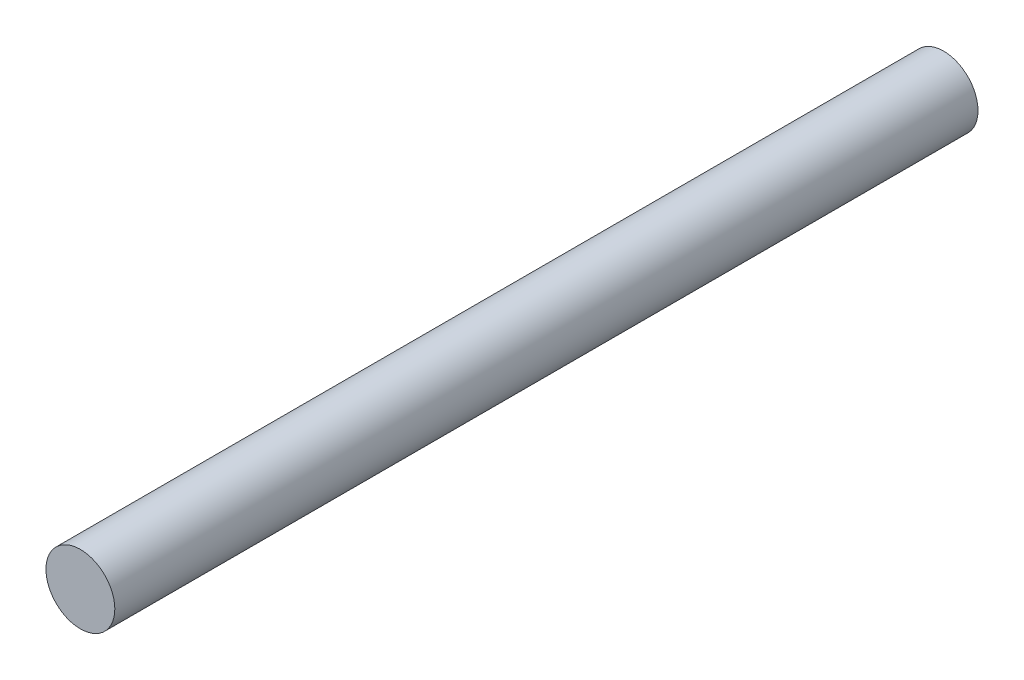
SolidWorks part; units mm, degrees
ref_plane "Front Plane" through (0, 0, 0) normal (0, 0, 1) x (1, 0, 0)
ref_plane "Top Plane" through (0, 0, 0) normal (0, 1, 0) x (1, 0, 0)
ref_plane "Right Plane" through (0, 0, 0) normal (1, 0, 0) x (0, 0, -1)
sketch "Sketch1" plane through (0, 0, 0) normal (0, 0, 1) x (1, 0, 0)
  circle A0 centre (0, 0) radius 0.9975
extrude "Boss-Extrude1" add sketch "Sketch1" along normal blind 25
